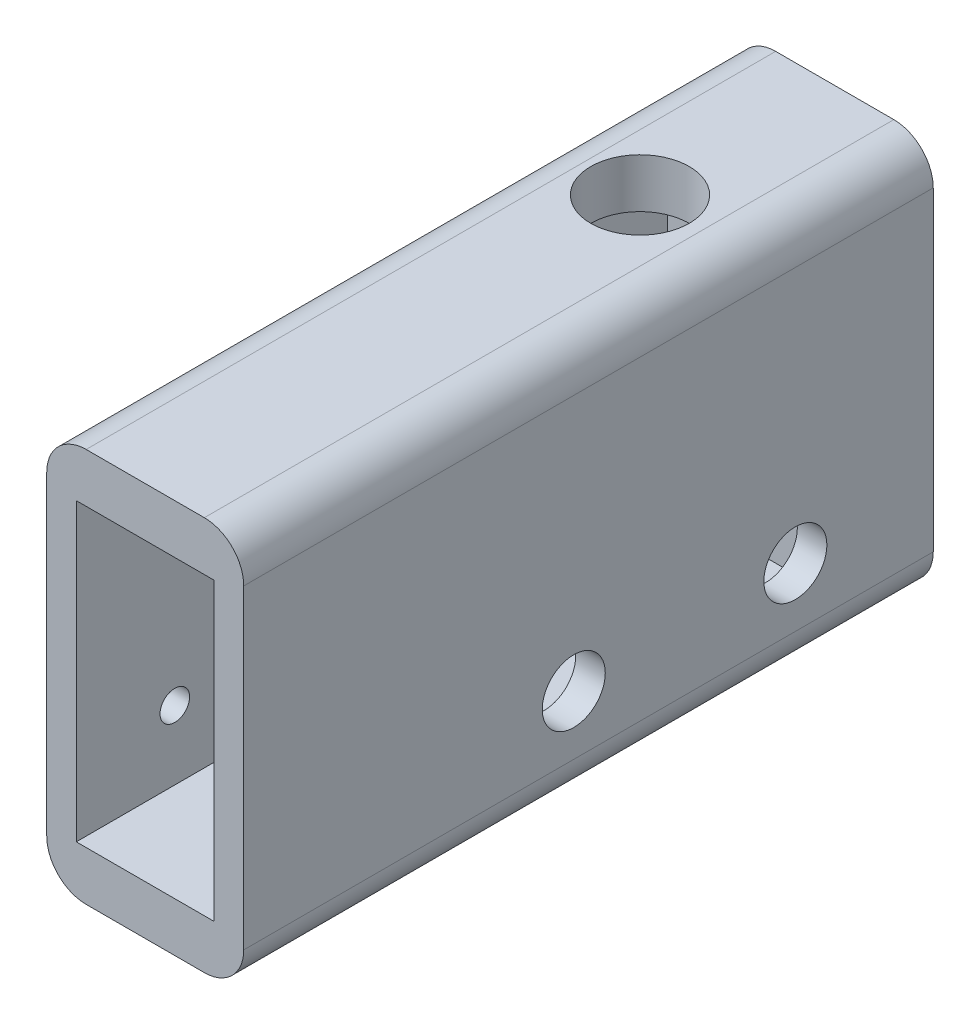
SolidWorks part; units mm, degrees
ref_plane "Plan de face" through (0, 0, 0) normal (0, 0, 1) x (1, 0, 0)
ref_plane "Plan de dessus" through (0, 0, 0) normal (0, 1, 0) x (1, 0, 0)
ref_plane "Plan de droite" through (0, 0, 0) normal (1, 0, 0) x (0, 0, -1)
sketch "Esquisse1" plane through (0, 0, 0) normal (0, 0, 1) x (1, 0, 0)
  line L1 (0, 0) -> (10, 0)
  line L2 (0, 0) -> (0, 20)
  line L3 (0, 20) -> (10, 20)
  line L4 (10, 0) -> (10, 20)
  dimension "D1" = 20
  dimension "D2" = 10
extrude "Boss.-Extru.1" add sketch "Esquisse1" along normal blind 35
sketch "Esquisse2" plane through (0, 0, 35) normal (0, 0, 1) x (1, 0, 0)
  line L0 (0, 20) -> (0, 0) construction
  line L1 (1.5, 2.5) -> (8.5, 2.5)
  line L2 (1.5, 2.5) -> (1.5, 17.5)
  line L3 (1.5, 17.5) -> (8.5, 17.5)
  line L4 (8.5, 2.5) -> (8.5, 17.5)
  line L5 (10, 20) -> (0, 20) construction
  dimension "D1" = 15
  dimension "D2" = 7
  dimension "D3" = 1.5
  dimension "D4" = 2.5
extrude "Enlèv. mat.-Extru.1" cut sketch "Esquisse2" against normal blind 30
sketch "Esquisse3" plane through (0, 0, 5) normal (0, 0, 1) x (1, 0, 0)
  line L0 (0, 20) -> (0, 0) construction
  line L1 (0, 0) -> (10, 0) construction
  circle A0 centre (5, 14.5274) radius 1.55
  circle A1 centre (5, 6.2802) radius 1.55
  dimension "D1" = 3.1
  dimension "D2" = 3.1
  dimension "D4" = 5
  dimension "D5" = 8.2471
  dimension "D6" = 6.2802
  dimension "D3" = 5
extrude "Enlèv. mat.-Extru.2" cut sketch "Esquisse3" against normal through all
sketch "Esquisse4" plane through (0, 20, 0) normal (0, 1, 0) x (1, 0, 0)
  circle A0 centre (4.8684, -9.7546) radius 2.5
  dimension "D1" = 5
extrude "Enlèv. mat.-Extru.3" cut sketch "Esquisse4" against normal blind 5
sketch "Esquisse5" plane through (0, 0, 0) normal (-1, 0, 0) x (0, 0, 1)
  line L0 (35, 20) -> (35, 0) construction
  line L1 (35, 20) -> (0, 20) construction
  line L2 (35, 0) -> (0, 0) construction
  circle A0 centre (30, 14) radius 0.75
  circle A1 centre (30, 6) radius 0.75
  dimension "D1" = 1.5
  dimension "D2" = 1.5
  dimension "D3" = 5
  dimension "D4" = 5
  dimension "D5" = 6
  dimension "D6" = 6
extrude "Enlèv. mat.-Extru.4" cut sketch "Esquisse5" against normal blind 2.5
fillet "Congé1" radius 2 4 edges at (10, 20, 17.5) (10, 0, 17.5) (0, 0, 17.5) (0, 20, 17.5)
sketch "Esquisse6" plane through (10, 0, 0) normal (1, 0, 0) x (0, 0, -1)
  line L0 (-35, 2) -> (0, 2) construction
  line L1 (0, 2) -> (0, 18) construction
  circle A0 centre (-7, 5) radius 1.6
  circle A1 centre (-18.2481, 5) radius 1.6
  dimension "D1" = 3.2
  dimension "D2" = 3.2
  dimension "D3" = 3
  dimension "D4" = 3
  dimension "D5" = 7
extrude "Enlèv. mat.-Extru.5" cut sketch "Esquisse6" against normal through all
